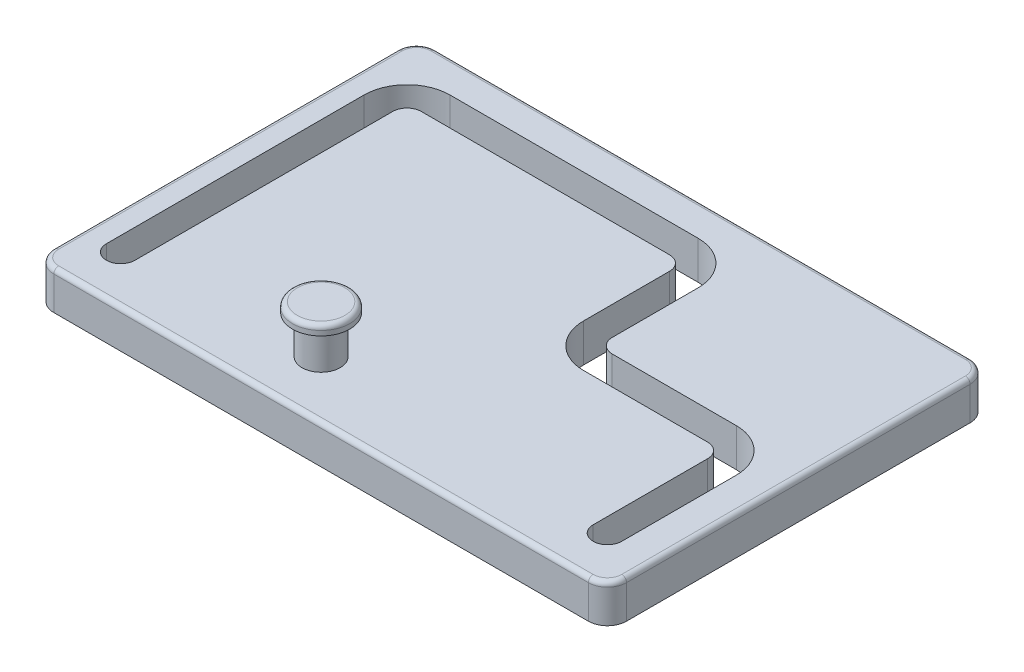
SolidWorks part; units mm, degrees
ref_plane "Front Plane" through (0, 0, 0) normal (0, 0, 1) x (1, 0, 0)
ref_plane "Top Plane" through (0, 0, 0) normal (0, 1, 0) x (1, 0, 0)
ref_plane "Right Plane" through (0, 0, 0) normal (1, 0, 0) x (0, 0, -1)
sketch "Sketch1" plane through (0, 0, 0) normal (0, 1, 0) x (1, 0, 0)
  line L1 (-140, 100) -> (140, 100)
  line L2 (-150, 90) -> (-150, -90)
  line L3 (-140, -100) -> (140, -100)
  line L4 (150, 90) -> (150, -90)
  line L5 (-150, 100) -> (150, -100) construction
  line L6 (-150, -100) -> (150, 100) construction
  arc A0 (140, 100) -> (150, 90) centre (140, 90) cw
  arc A1 (-150, -90) -> (-140, -100) centre (-140, -90) ccw
  arc A2 (-140, 100) -> (-150, 90) centre (-140, 90) ccw
  arc A3 (140, -100) -> (150, -90) centre (140, -90) ccw
  point P0 (0, 0)
  dimension "D3" = 10
  dimension "D1" = 300
  dimension "D2" = 200
extrude "Boss-Extrude1" add sketch "Sketch1" along normal blind 20
fillet "Fillet1" radius 2.5 8 edges at (150, 20, 0) (147.0711, 20, 97.0711) (0, 20, 100) (-147.0711, 20, 97.0711) (-150, 20, 0) (-147.0711, 20, -97.0711) (0, 20, -100) (147.0711, 20, -97.0711)
sketch "Sketch3" plane through (0, 20, 0) normal (0, 1, 0) x (1, 0, 0)
  line L0 (-130, -75) -> (-130, 60) construction
  line L1 (-115, 75) -> (15, 75) construction
  line L2 (30, 60) -> (30, 15) construction
  line L3 (45, 0) -> (110, 0) construction
  line L4 (125, -15) -> (125, -75) construction
  line L5 (-150, -90) -> (-150, 90) construction
  line L6 (-140, 100) -> (140, 100) construction
  line L7 (150, 90) -> (150, -90) construction
  line L8 (140, -100) -> (-140, -100) construction
  line L9 (-122.5, -75) -> (-122.5, 60)
  line L10 (-115, 67.5) -> (15, 67.5)
  line L11 (22.5, 60) -> (22.5, 15)
  line L12 (45, -7.5) -> (110, -7.5)
  line L13 (117.5, -15) -> (117.5, -75)
  line L14 (-137.5, -75) -> (-137.5, 60)
  line L15 (-115, 82.5) -> (15, 82.5)
  line L16 (37.5, 60) -> (37.5, 15)
  line L17 (45, 7.5) -> (110, 7.5)
  line L18 (132.5, -15) -> (132.5, -75)
  arc A0 (110, 0) -> (125, -15) centre (110, -15) cw construction
  arc A1 (30, 15) -> (45, 0) centre (45, 15) ccw construction
  arc A2 (15, 75) -> (30, 60) centre (15, 60) cw construction
  arc A3 (-130, 60) -> (-115, 75) centre (-115, 60) cw construction
  arc A4 (-122.5, 60) -> (-115, 67.5) centre (-115, 60) cw
  arc A5 (15, 67.5) -> (22.5, 60) centre (15, 60) cw
  arc A6 (22.5, 15) -> (45, -7.5) centre (45, 15) ccw
  arc A7 (110, -7.5) -> (117.5, -15) centre (110, -15) cw
  arc A8 (-137.5, 60) -> (-115, 82.5) centre (-115, 60) cw
  arc A9 (15, 82.5) -> (37.5, 60) centre (15, 60) cw
  arc A10 (37.5, 15) -> (45, 7.5) centre (45, 15) ccw
  arc A11 (110, 7.5) -> (132.5, -15) centre (110, -15) cw
  arc A12 (-122.5, -75) -> (-137.5, -75) centre (-130, -75) cw
  arc A13 (117.5, -75) -> (132.5, -75) centre (125, -75) ccw
  point P17 (30, 0)
  dimension "D4" = 15
  dimension "D1" = 20
  dimension "D2" = 25
  dimension "D3" = 25
  dimension "D5" = 25
  dimension "D8" = 30
  dimension "D6" = 7.5
  dimension "D7" = 7.5
extrude "Cut-Extrude1" cut sketch "Sketch3" against normal up to next
sketch "Sketch4" plane through (0, 20, 0) normal (0, 1, 0) x (1, 0, 0)
  line L0 (140, -100) -> (-140, -100) construction
  circle A0 centre (-30, -70) radius 10
  dimension "D1" = 20
  dimension "D2" = 30
  dimension "D3" = 30
extrude "Boss-Extrude2" add sketch "Sketch4" along normal blind 20
sketch "Sketch5" plane through (0, 40, 0) normal (0, 1, 0) x (1, 0, 0)
  circle A0 centre (-30, -70) radius 15
  dimension "D1" = 30
extrude "Boss-Extrude3" add sketch "Sketch5" along normal blind 5
fillet "Fillet2" radius 2.5 1 edges at (-30, 45, 85)
sketch "Sketch6" plane through (0, 20, 0) normal (0, 1, 0) x (1, 0, 0)
  line L31 (-130, 60) -> (-130, -75)
  line L32 (125, -75) -> (125, -15)
  line L33 (110, 0) -> (45, 0)
  line L34 (30, 15) -> (30, 60)
  line L35 (15, 75) -> (-115, 75)
  line L36 (-130, 60) -> (-130, -75)
  line L37 (125, -75) -> (125, -15)
  line L38 (110, 0) -> (45, 0)
  line L39 (30, 15) -> (30, 60)
  line L40 (15, 75) -> (-115, 75)
  arc A34 (125, -15) -> (110, 0) centre (110, -15) ccw
  arc A35 (30, 15) -> (45, 0) centre (45, 15) ccw
  arc A36 (30, 60) -> (15, 75) centre (15, 60) ccw
  arc A37 (-115, 75) -> (-130, 60) centre (-115, 60) ccw
  arc A38 (125, -15) -> (110, 0) centre (110, -15) ccw
  arc A39 (30, 15) -> (45, 0) centre (45, 15) ccw
  arc A40 (30, 60) -> (15, 75) centre (15, 60) ccw
  arc A41 (-115, 75) -> (-130, 60) centre (-115, 60) ccw
  dimension "D1" = 7.5
sketch "Sketch8" plane through (0, 20, 0) normal (0, 1, 0) x (1, 0, 0)
  line L30 (125, -75) -> (125, -15)
  line L31 (110, 0) -> (45, 0)
  line L32 (30, 15) -> (30, 60)
  line L33 (15, 75) -> (-115, 75)
  line L34 (-130, 60) -> (-130, -75)
  line L35 (125, -75) -> (125, -15)
  line L36 (110, 0) -> (45, 0)
  line L37 (30, 15) -> (30, 60)
  line L38 (15, 75) -> (-115, 75)
  line L39 (-130, 60) -> (-130, -75)
  arc A24 (125, -15) -> (110, 0) centre (110, -15) ccw
  arc A25 (30, 15) -> (45, 0) centre (45, 15) ccw
  arc A26 (30, 60) -> (15, 75) centre (15, 60) ccw
  arc A27 (-115, 75) -> (-130, 60) centre (-115, 60) ccw
  arc A28 (125, -15) -> (110, 0) centre (110, -15) ccw
  arc A29 (30, 15) -> (45, 0) centre (45, 15) ccw
  arc A30 (30, 60) -> (15, 75) centre (15, 60) ccw
  arc A31 (-115, 75) -> (-130, 60) centre (-115, 60) ccw
  dimension "D1" = 7.5
sketch "Sketch9" plane through (0, 20, 0) normal (0, 1, 0) x (1, 0, 0)
  line L0 (132.5, -75) -> (132.5, -15) construction
  line L1 (110, 7.5) -> (45, 7.5) construction
  line L2 (37.5, 15) -> (37.5, 60) construction
  line L3 (-137.5, 60) -> (-137.5, -75) construction
  line L4 (15, 82.5) -> (-115, 82.5) construction
  line L5 (132.5, -75) -> (132.5, -15)
  line L6 (110, 7.5) -> (45, 7.5)
  line L7 (37.5, 15) -> (37.5, 60)
  line L8 (-137.5, 60) -> (-137.5, -75)
  line L9 (15, 82.5) -> (-115, 82.5)
  line L10 (125, -75) -> (125, -15)
  line L11 (110, 0) -> (45, 0)
  line L12 (30, 15) -> (30, 60)
  line L13 (15, 75) -> (-115, 75)
  line L14 (-130, 60) -> (-130, -75)
  arc A0 (132.5, -15) -> (110, 7.5) centre (110, -15) ccw construction
  arc A1 (37.5, 15) -> (45, 7.5) centre (45, 15) ccw construction
  arc A2 (37.5, 60) -> (15, 82.5) centre (15, 60) ccw construction
  arc A3 (-115, 82.5) -> (-137.5, 60) centre (-115, 60) ccw construction
  arc A4 (132.5, -15) -> (110, 7.5) centre (110, -15) ccw
  arc A5 (37.5, 15) -> (45, 7.5) centre (45, 15) ccw
  arc A6 (37.5, 60) -> (15, 82.5) centre (15, 60) ccw
  arc A7 (-115, 82.5) -> (-137.5, 60) centre (-115, 60) ccw
  arc A8 (125, -15) -> (110, 0) centre (110, -15) ccw
  arc A9 (30, 15) -> (45, 0) centre (45, 15) ccw
  arc A10 (30, 60) -> (15, 75) centre (15, 60) ccw
  arc A11 (-115, 75) -> (-130, 60) centre (-115, 60) ccw
  dimension "D1" = 7.5
